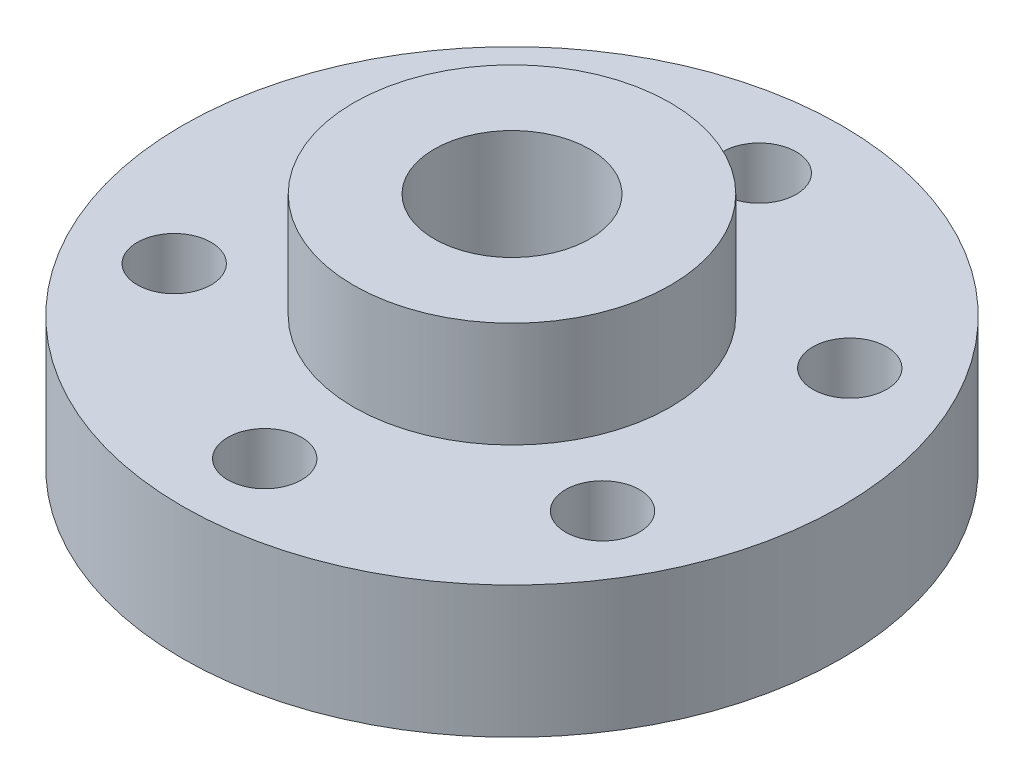
SolidWorks part; units mm, degrees
ref_plane "Front Plane" through (0, 0, 0) normal (0, 0, 1) x (1, 0, 0)
ref_plane "Top Plane" through (0, 0, 0) normal (0, 1, 0) x (1, 0, 0)
ref_plane "Right Plane" through (0, 0, 0) normal (1, 0, 0) x (0, 0, -1)
sketch "Sketch1" plane through (0, 0, 0) normal (0, 0, 1) x (1, 0, 0)
  line L0 (0, 0) -> (0, 15.9602) construction
  line L1 (2.9972, 0) -> (12.7, 0)
  line L2 (12.7, 0) -> (12.7, 5.08)
  line L3 (12.7, 5.08) -> (6.096, 5.08)
  line L4 (6.096, 5.08) -> (6.096, 9.144)
  line L5 (6.096, 9.144) -> (2.9972, 9.144)
  line L6 (2.9972, 9.144) -> (2.9972, 0)
  dimension "D1" = 9.144
  dimension "D2" = 5.9944
  dimension "D3" = 12.192
  dimension "D4" = 25.4
  dimension "D5" = 5.08
revolve "Revolve1" add sketch "Sketch1" angle 360 about L0
sketch "Sketch2" plane through (0, 0, 0) normal (0, 1, 0) x (1, 0, 0)
  line L0 (0, 0) -> (0, 12.7) construction
  circle A0 centre (0, 0) radius 12.7 construction
  circle A1 centre (0, 9.525) radius 1.4224
  dimension "D1" = 2.8448
  dimension "D2" = 9.525
extrude "Cut-Extrude1" cut sketch "Sketch2" along normal through all
pattern_circular "CirPattern1" count 6 over 360 about axis through (0, 0, 0) along (0, 1, 0) of "Cut-Extrude1"
